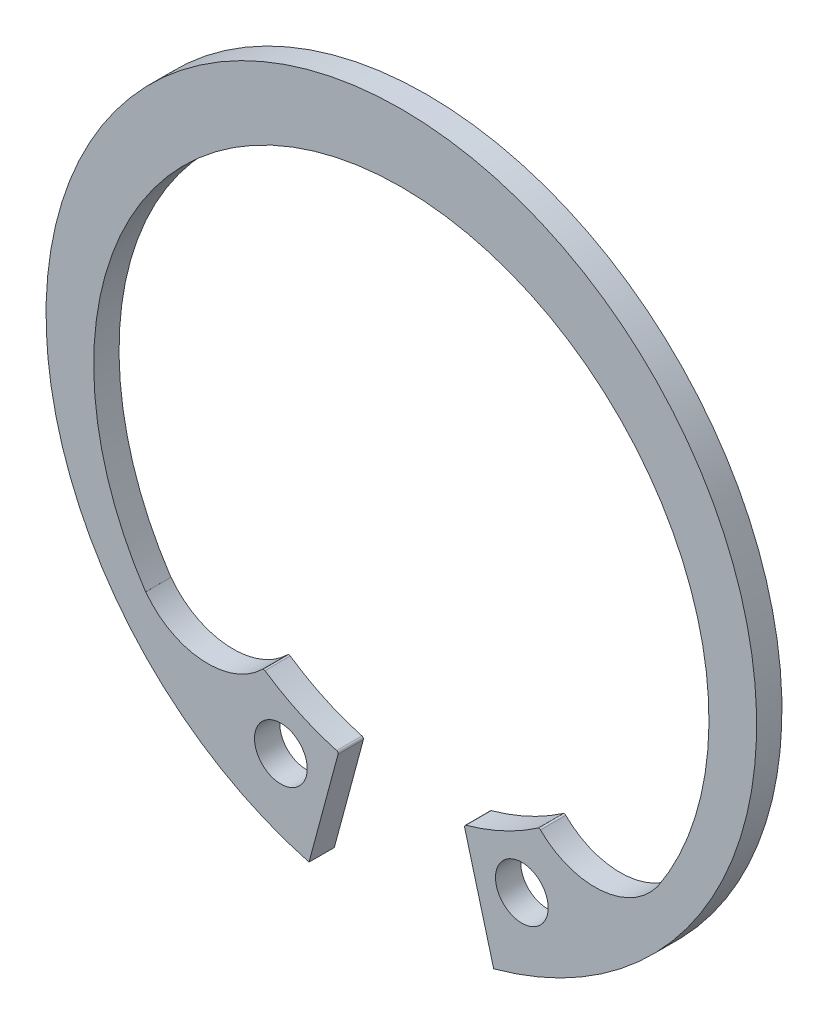
SolidWorks part; units mm, degrees
ref_plane "Plane1" through (0, 0, 0) normal (0, 0, 1) x (1, 0, 0)
ref_plane "Plane2" through (0, 0, 0) normal (0, 1, 0) x (1, 0, 0)
ref_plane "Plane3" through (0, 0, 0) normal (1, 0, 0) x (0, 0, -1)
extrude "Body" add sketch "BodySke" against normal blind 1.2
sketch "BodySke" plane through (0, 0, 0) normal (0, 0, 1) x (1, 0, 0)
  line L0 (-1.5431, 0) -> (1.5431, 0) construction
  line L1 (0, 0) -> (0, 13.65) construction
  line L2 (4.3788, -16.2711) -> (3.5174, -13.0701)
  line L3 (-4.3788, -16.2711) -> (-3.5174, -13.0701)
  line L4 (0, 0) -> (11.6973, -12.1283) construction
  line L5 (0, 0) -> (-11.6973, -12.1283) construction
  line L6 (-5.3894, -11.2719) -> (-6.039, -13.686) construction
  line L7 (5.5192, -11.7541) -> (5.9093, -13.2037) construction
  arc A0 (-3.5174, -13.0701) -> (-7.3598, -10.9081) centre (-5.7142, -12.4789) ccw
  arc A1 (7.3598, -10.9081) -> (3.5174, -13.0701) centre (5.7142, -12.4789) ccw
  arc A2 (10.5866, -10.9766) -> (-10.5866, -10.9766) centre (0, -0.9388) ccw construction
  arc A3 (4.3788, -16.2711) -> (-4.3788, -16.2711) centre (0, 0) ccw
  circle A4 centre (5.7142, -12.4789) radius 1.25
  circle A5 centre (-5.7142, -12.4789) radius 1.25
  circle A6 centre (5.7142, -12.4789) radius 2.275 construction
  arc A7 (10.6692, -10.8888) -> (-10.6692, -10.8888) centre (0, -0.9388) ccw
  arc A8 (-5.7142, -12.4789) -> (5.7142, -12.4789) centre (0, 0) ccw construction
  arc A9 (-10.6692, -10.8888) -> (-7.3598, -10.9081) centre (-9.0054, -9.3372) ccw
  arc A10 (7.3598, -10.9081) -> (10.6692, -10.8888) centre (9.0054, -9.3372) ccw
  dimension "GrooveDia" = 33.7
  dimension "TipRad" = 2.275
  dimension "HoleOffsetRad" = 13.725
  dimension "HoleDia" = 2.5
  dimension "FilletRad" = 2.275
  dimension "LargeRad" = 13.65
  dimension "SmallRad" = 15.25
  dimension "SmallAngle" = 87.928
  dimension "GapAngle" = 30.125
sketch "Clipboard" plane through (0, 0, 0) normal (0, 0, 1) x (1, 0, 0)
  line L0 (0, 0) -> (3.2, 0)
  line L1 (0, 0) -> (0, 1.6)
  line L2 (0, 0) -> (0, -5.4)
  circle A0 centre (0, 0) radius 1.25
  circle A1 centre (0, 0) radius 16
  dimension "HoleDia" = 2.5
  dimension "BoreDia" = 32
  dimension "LargeSection" = 3.2
  dimension "SmallSection" = 1.6
  dimension "LugSection" = 5.4
sketch "ModLugSke" plane through (0, 0, 0) normal (0, 0, 1) x (1, 0, 0)
  line L0 (4.3788, -16.2711) -> (3.0014, -11.1528)
  line L1 (-4.3788, -16.2711) -> (-3.0014, -11.1528)
  line L2 (9.1782, -6.8457) -> (13.5068, -10.0742) construction
  line L3 (-9.1782, -6.8457) -> (-13.5068, -10.0742) construction
  line L4 (-4.3788, -16.2711) -> (-3.5174, -13.0701) construction
  line L5 (3.5174, -13.0701) -> (4.3788, -16.2711) construction
  line L6 (0, 0) -> (0, -18.0732) construction
  line L7 (12.1234, -9.0423) -> (13.5068, -10.0742)
  line L8 (-13.5068, -10.0742) -> (-12.1234, -9.0423)
  arc A0 (4.3788, -16.2711) -> (13.5068, -10.0742) centre (0, 0) ccw
  arc A1 (-6.4688, -9.4476) -> (-3.0711, -11.0304) centre (0, 0) ccw
  arc A2 (4.3788, -16.2711) -> (-4.3788, -16.2711) centre (0, 0) ccw construction
  arc A3 (7.3598, -10.9081) -> (3.5174, -13.0701) centre (5.7142, -12.4789) ccw construction
  arc A4 (-6.4688, -9.4476) -> (-6.5956, -9.459) centre (-6.5253, -9.5301) ccw
  arc A5 (-12.1234, -9.0423) -> (-6.5956, -9.459) centre (-9.1782, -6.8457) ccw
  arc A6 (10.6692, -10.8888) -> (-10.6692, -10.8888) centre (0, -0.9388) ccw construction
  arc A7 (6.5956, -9.459) -> (12.1234, -9.0423) centre (9.1782, -6.8457) ccw
  arc A8 (3.0711, -11.0304) -> (6.4688, -9.4476) centre (0, 0) ccw
  arc A9 (-13.5068, -10.0742) -> (-4.3788, -16.2711) centre (0, 0) ccw
  circle A10 centre (-5.7142, -12.4789) radius 1.25
  circle A11 centre (-5.7142, -12.4789) radius 1.25 construction
  circle A12 centre (5.7142, -12.4789) radius 1.25
  circle A13 centre (5.7142, -12.4789) radius 1.25 construction
  arc A14 (-3.0711, -11.0304) -> (-3.0014, -11.1528) centre (-3.0979, -11.1268) cw
  arc A15 (3.0711, -11.0304) -> (3.0014, -11.1528) centre (3.0979, -11.1268) ccw
  arc A16 (6.4688, -9.4476) -> (6.5956, -9.459) centre (6.5253, -9.5301) cw
  point P43 (2.9755, -11.0566)
  dimension "D1" = 0.1
  dimension "LugAng" = 68.799
extrude "ModLug" add sketch "ModLugSke" against normal through all
sketch "UnlSke" [suppressed] plane through (0, 0, 0) normal (0, 0, 1) x (1, 0, 0)
  line L0 (2.1178, -8.3352) -> (3.2259, -12.6966)
  line L1 (-2.1178, -8.3352) -> (-3.2259, -12.6966)
  line L2 (-3.2259, -12.6966) -> (-2.1422, -8.4315) construction
  line L3 (2.1422, -8.4315) -> (3.2259, -12.6966) construction
  arc A0 (2.1178, -8.3352) -> (-2.1178, -8.3352) centre (0, 0) ccw
  arc A1 (3.2259, -12.6966) -> (-3.2259, -12.6966) centre (0, 0) ccw
  arc A2 (3.2259, -12.6966) -> (-3.2259, -12.6966) centre (0, 0) ccw construction
  circle A4 centre (-4.4431, -9.5688) radius 1
  circle A5 centre (4.4431, -9.5688) radius 1
  circle A6 centre (4.4431, -9.5688) radius 1 construction
  circle A7 centre (-4.4431, -9.5688) radius 1 construction
  arc A8 (2.2134, -8.3103) -> (4.9183, -7.0548) centre (0, 0) ccw construction
extrude "Unlug" [suppressed] add sketch "UnlSke" against normal through all
equation "' \"BoreDia@Clipboard\" = 8"
equation "' \"Thickness@Body\" = 0.8"
equation "' \"GrooveDia@BodySke\" = 8.4"
equation "' \"LugSection@Clipboard\" = 2.4"
equation "' \"LargeSection@Clipboard\" = 1.1"
equation "' \"HoleDia@Clipboard\" = 1.0"
equation "' \"BoreDia@Clipboard\" = 25"
equation "' \"Thickness@Body\" = 1.2"
equation "' \"GrooveDia@BodySke\" = 26.2"
equation "' \"LugSection@Clipboard\" = 4.5"
equation "' \"LargeSection@Clipboard\" = 2.7"
equation "' \"HoleDia@Clipboard\" = 2"
equation "\"SmallSection@Clipboard\" = \"LargeSection@Clipboard\" * 0.5"
equation "\"TipRad@BodySke\" = (\"LugSection@Clipboard\" - (\"GrooveDia@BodySke\" / 2  -  \"BoreDia@Clipboard\" / 2 ) ) / 2"
equation "\"HoleOffsetRad@BodySke\" = (\"GrooveDia@BodySke\" / 2) - \"LugSection@Clipboard\"  + \"TipRad@BodySke\""
equation "\"LargeRad@BodySke\" =  \"GrooveDia@BodySke\" / 2 -  \"LargeSection@Clipboard\""
equation "\"SmallRad@BodySke\" =  \"GrooveDia@BodySke\" / 2 -  \"SmallSection@Clipboard\""
equation "\"HoleDia@BodySke\" =  \"HoleDia@Clipboard\""
equation "\"FilletRad@BodySke\" = \"TipRad@BodySke\" * 1.0"
equation "\"GapAngle@BodySke\" = 360 - 0.965 * 360 * ( \"BoreDia@Clipboard\" /  \"GrooveDia@BodySke\")"
equation "\"LugAng@ModLugSke\" = \"GapAngle@BodySke\"  + 2 * 360 * (\"LugSection@Clipboard\" / (\"BoreDia@Clipboard\" * 3.1416))"
